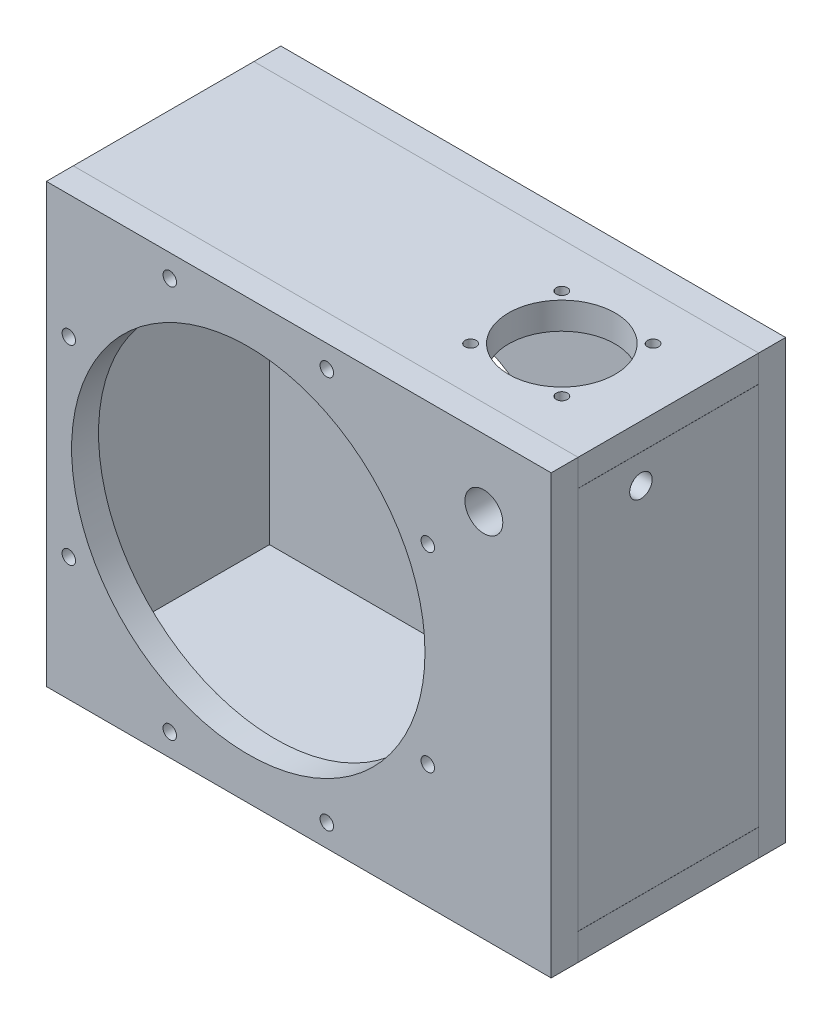
SolidWorks part; units mm, degrees
ref_plane "前视基准面" through (0, 0, 0) normal (0, 0, 1) x (1, 0, 0)
ref_plane "上视基准面" through (0, 0, 0) normal (0, 1, 0) x (1, 0, 0)
ref_plane "右视基准面" through (0, 0, 0) normal (1, 0, 0) x (0, 0, -1)
sketch "草图1" plane through (0, 0, 0) normal (0, 0, 1) x (1, 0, 0)
  line L1 (0, 0) -> (450, 0)
  line L2 (0, 0) -> (0, -390)
  line L3 (0, -390) -> (450, -390)
  line L4 (450, 0) -> (450, -390)
  dimension "D1" = 450
  dimension "D2" = 390
extrude "拉伸1" add sketch "草图1" along normal blind 24
sketch "草图2" plane through (0, 0, 24) normal (0, 0, 1) x (1, 0, 0)
  line L0 (24, -24) -> (24, -366)
  line L1 (0, 0) -> (450, 0)
  line L2 (0, 0) -> (0, -390)
  line L3 (0, -390) -> (450, -390)
  line L4 (450, 0) -> (450, -390)
  line L5 (24, -366) -> (426, -366)
  line L6 (426, -24) -> (426, -366)
  line L7 (24, -24) -> (426, -24)
  dimension "D1" = 24
extrude "拉伸2" add sketch "草图2" along normal blind 161 separate body
sketch "草图3" plane through (0, 0, 185) normal (0, 0, 1) x (1, 0, 0)
  line L1 (0, 0) -> (450, 0)
  line L2 (0, 0) -> (0, -390)
  line L3 (0, -390) -> (450, -390)
  line L4 (450, 0) -> (450, -390)
  dimension "D1" = 390
extrude "拉伸3" add sketch "草图3" along normal blind 24 separate body
sketch "草图4" plane through (0, 0, 209) normal (0, 0, 1) x (1, 0, 0)
  line L0 (0, 0) -> (0, -390) construction
  line L1 (0, -390) -> (450, -390) construction
  circle A0 centre (180, -195) radius 157.5
  dimension "D1" = 180
  dimension "D2" = 315
  dimension "D3" = 195
sketch "草图5" plane through (0, -390, 0) normal (0, -1, 0) x (1, 0, 0)
  line L0 (450, 24) -> (450, 0) construction
  line L1 (0, 209) -> (450, 209) construction
  circle A0 centre (355, 104.5) radius 47.5
  dimension "D2" = 104.5
  dimension "D1" = 95
  dimension "D3" = 95
sketch "草图6" plane through (0, 0, 0) normal (0, 0, -1) x (-1, 0, 0)
  line L0 (0, -390) -> (-450, -390) construction
  circle A0 centre (-180, -195) radius 82.5
  dimension "D1" = 165
  dimension "D2" = 195
extrude "切除-拉伸3" cut sketch "草图6" against normal blind 33
sketch "草图9" plane through (0, 0, 0) normal (0, 0, -1) x (-1, 0, 0)
  circle A1 centre (-180, -102.5) radius 4
  circle A2 centre (-125.6299, -120.1659) radius 4
  circle A3 centre (-92.0273, -166.4159) radius 4
  circle A4 centre (-92.0273, -223.5841) radius 4
  circle A5 centre (-125.6299, -269.8341) radius 4
  circle A6 centre (-180, -287.5) radius 4
  circle A7 centre (-234.3701, -269.8341) radius 4
  circle A8 centre (-267.9727, -223.5841) radius 4
  circle A9 centre (-267.9727, -166.4159) radius 4
  circle A10 centre (-234.3701, -120.1659) radius 4
  dimension "D1" = 8
extrude "切除-拉伸4" cut sketch "草图9" against normal blind 18
extrude "切除-拉伸5" cut sketch "草图4" against normal blind 43
extrude "切除-拉伸6" cut sketch "草图5" against normal blind 43
sketch "草图10" plane through (0, -390, 0) normal (0, -1, 0) x (1, 0, 0)
  circle A1 centre (395.6586, 145.1586) radius 5
  circle A2 centre (395.6586, 63.8414) radius 5
  circle A3 centre (314.3414, 63.8414) radius 5
  circle A4 centre (314.3414, 145.1586) radius 5
  dimension "D1" = 10
extrude "切除-拉伸7" cut sketch "草图10" against normal blind 18
sketch "草图11" plane through (0, 0, 0) normal (-1, 0, 0) x (0, 0, 1)
  line L1 (185, 0) -> (185, -390) construction
  line L2 (185, 0) -> (24, 0) construction
  line L3 (185, -24.1) -> (185, -24)
  line L4 (24, -24) -> (185, -24)
  line L6 (24, -24.1) -> (185, -24.1)
  line L7 (24, -24.1) -> (24, -24)
  line L9 (24, -365.9) -> (24, -366)
  line L10 (24, -365.9) -> (185, -365.9)
  line L11 (24, -366) -> (185, -366)
  line L12 (185, -365.9) -> (185, -366)
  line L13 (185, -390) -> (24, -390) construction
  dimension "D1" = 0.1
  dimension "D2" = 24
  dimension "D3" = 0.1
  dimension "D4" = 24
extrude "切除-拉伸8" cut sketch "草图11" against normal through all
sketch "草图12" plane through (0, 0, 0) normal (0, 1, 0) x (1, 0, 0)
  circle A0 centre (355, -104.5) radius 47.5
  dimension "D1" = 95
extrude "切除-拉伸9" cut sketch "草图12" against normal blind 40.2
sketch "草图13" plane through (0, 0, 0) normal (0, 1, 0) x (1, 0, 0)
  circle A0 centre (395.6586, -145.1586) radius 5
  circle A1 centre (314.3414, -145.1586) radius 5
  circle A2 centre (395.6586, -63.8414) radius 5
  circle A3 centre (314.3414, -63.8414) radius 5
extrude "切除-拉伸10" cut sketch "草图13" against normal blind 18
ref_plane "基准面1" through (0, 0, 24) normal (0, 0, -1) x (-1, 0, 0)
sketch "草图14" plane through (0, 0, 24) normal (0, 0, -1) x (-1, 0, 0)
  line L0 (0, -366) -> (-450, -366) construction
  line L1 (-24, -24.1) -> (-14, -24.1)
  line L2 (-24, -24.1) -> (-24, -366)
  line L3 (-24, -366) -> (-14, -366)
  line L4 (-14, -24.1) -> (-14, -366)
  line L5 (0, 0) -> (0, -390) construction
  line L8 (-436, -24.1) -> (-436, -366)
  line L9 (-426, -366) -> (-436, -366)
  line L10 (-426, -24.1) -> (-426, -366)
  line L11 (-426, -24.1) -> (-436, -24.1)
  dimension "D1" = 14
extrude "切除-拉伸12" cut sketch "草图14" against normal blind 161
sketch "草图17" plane through (0, -390, 0) normal (0, -1, 0) x (1, 0, 0)
  line L0 (70, 194.5) -> (200, 194.5) construction
  line L1 (70, 194.5) -> (70, 14.5) construction
  line L2 (0, 0) -> (450, 0) construction
  line L3 (0, 209) -> (450, 209) construction
  line L4 (0, 185) -> (0, 24) construction
  line L5 (0, 209) -> (0, 185) construction
  circle A0 centre (70, 194.5) radius 4
  circle A1 centre (200, 194.5) radius 4
  circle A2 centre (70, 14.5) radius 4
  circle A3 centre (200, 14.5) radius 4
  dimension "D2" = 8
  dimension "D3" = 14.5
  dimension "D4" = 200
  dimension "D5" = 70
  dimension "D6" = 70
  dimension "D7" = 14.5
  dimension "D1" = 90
extrude "切除-拉伸14" cut sketch "草图17" against normal blind 20
sketch "草图19" plane through (0, 0, 0) normal (0, 0, -1) x (-1, 0, 0)
  line L0 (-450, -390) -> (-450, 0) construction
  line L1 (-400, -15) -> (-225, -15) construction
  line L2 (-400, -15) -> (-400, -375) construction
  circle A0 centre (-400, -15) radius 8
  circle A1 centre (-225, -15) radius 8
  circle A2 centre (-50, -15) radius 8
  circle A3 centre (-400, -375) radius 8
  circle A4 centre (-225, -375) radius 8
  circle A5 centre (-50, -375) radius 8
  dimension "D1" = 16
  dimension "D2" = 50
  dimension "D3" = 90
extrude "切除-拉伸18" cut sketch "草图19" against normal blind 20
sketch "草图20" plane through (0, 0, 209) normal (0, 0, 1) x (1, 0, 0)
  circle A0 centre (110, -20) radius 6
  circle A1 centre (250, -20) radius 6
  circle A2 centre (110, -370) radius 6
  circle A3 centre (250, -370) radius 6
  circle A4 centre (20, -110) radius 6
  circle A5 centre (340, -110) radius 6
  circle A6 centre (20, -280) radius 6
  circle A7 centre (340, -280) radius 6
extrude "切除-拉伸19" cut sketch "草图20" against normal blind 20
sketch "草图21" plane through (450, 0, 0) normal (1, 0, 0) x (0, 0, -1)
  line L0 (-209, -390) -> (-209, 0) construction
  circle A0 centre (-129, -50) radius 10
  dimension "D1" = 80
extrude "切除-拉伸20" cut sketch "草图21" against normal blind 35
sketch "草图22" plane through (0, 0, 209) normal (0, 0, 1) x (1, 0, 0)
  line L0 (450, -390) -> (450, 0) construction
  line L1 (450, 0) -> (0, 0) construction
  circle A0 centre (390, -60) radius 16.875
  dimension "D1" = 60
  dimension "D2" = 60
  dimension "D3" = 33.75
extrude "切除-拉伸21" cut sketch "草图22" against normal blind 40
